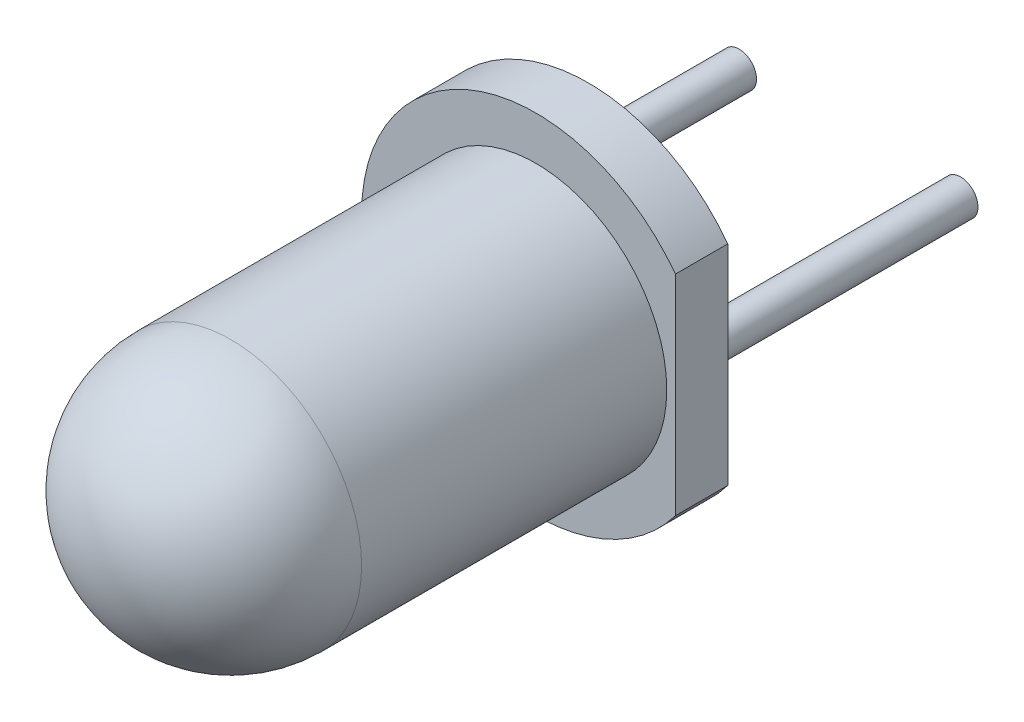
SolidWorks part; units mm, degrees
ref_plane "前视基准面" through (0, 0, 0) normal (0, 0, 1) x (1, 0, 0)
ref_plane "上视基准面" through (0, 0, 0) normal (0, 1, 0) x (1, 0, 0)
ref_plane "右视基准面" through (0, 0, 0) normal (1, 0, 0) x (0, 0, -1)
sketch "草图1" plane through (0, 0, 0) normal (0, 0, 1) x (1, 0, 0)
  line L0 (1.6, 1.2) -> (1.6, -1.2)
  arc A0 (1.6, 1.2) -> (1.6, -1.2) centre (0, 0) ccw
  circle A1 centre (0, 0) radius 1.6 construction
  dimension "D1" = 3.2
extrude "凸台-拉伸1" add sketch "草图1" along normal blind 0.6
sketch "草图2" plane through (0, 0, 0.6) normal (0, 0, 1) x (1, 0, 0)
  circle A0 centre (0, 0) radius 1.5
  dimension "D1" = 3
extrude "凸台-拉伸2" add sketch "草图2" along normal blind 5
fillet "圆角1" radius 1.5 1 edges at (1.5, 0, 5.6)
sketch "草图3" plane through (0, 0, 0) normal (0, 0, -1) x (-1, 0, 0)
  line L0 (-1.27, -2.5475) -> (-1.27, 2.6834) construction
  line L1 (0, -1000) -> (0, 49000) construction
  line L2 (-1.4702, -0.2) -> (-1.4702, 0.2) construction
  line L3 (-1000, 0) -> (49000, 0) construction
  line L4 (-1.4702, -0.2) -> (-1.0698, -0.2) construction
  line L5 (-1.4702, 0.2) -> (-1.0698, 0.2) construction
  line L6 (-1.0698, -0.2) -> (-1.0698, 0.2) construction
  line L7 (1.4702, 0.2) -> (1.0698, 0.2) construction
  line L8 (1.4702, -0.2) -> (1.4702, 0.2) construction
  line L9 (1.4702, -0.2) -> (1.0698, -0.2) construction
  line L10 (1.0698, -0.2) -> (1.0698, 0.2) construction
  line L11 (1.27, -0.2) -> (1.27, 0.2) construction
  line L12 (-1.27, -0.2) -> (-1.27, 0.2) construction
  circle A0 centre (1.27, 0) radius 0.2
  circle A1 centre (-1.27, 0) radius 0.2
  dimension "D1" = 1.27
  dimension "D2" = 0.2002
  dimension "D3" = 0.2
extrude "凸台-拉伸3" add sketch "草图3" along normal blind 3
